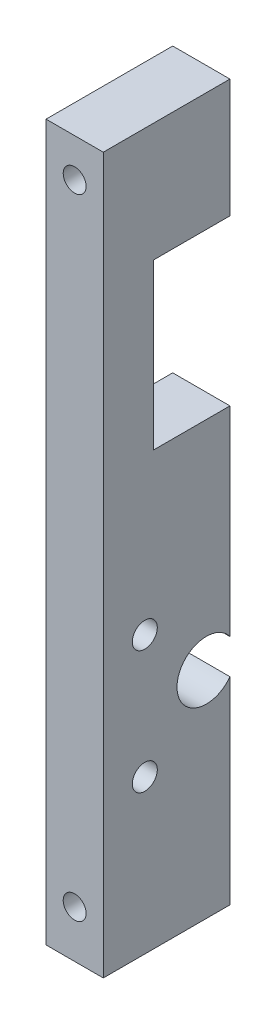
SolidWorks part; units mm, degrees
material "6061-T6 (SS)"
ref_plane "前视基准面" through (0, 0, 0) normal (0, 0, 1) x (1, 0, 0)
ref_plane "上视基准面" through (0, 0, 0) normal (0, 1, 0) x (1, 0, 0)
ref_plane "右视基准面" through (0, 0, 0) normal (1, 0, 0) x (0, 0, -1)
other "Configuration Table"
sketch "草图1" plane through (0, 0, 0) normal (0, 0, 1) x (1, 0, 0)
  line L1 (49.65, -4.3) -> (53.65, -4.3)
  line L2 (49.65, -4.3) -> (49.65, 45.68)
  line L3 (49.65, 45.68) -> (53.65, 45.68)
  line L4 (53.65, -4.3) -> (53.65, 45.68)
  dimension "D1" = 49.65
  dimension "D2" = 53.65
  dimension "D3" = 45.68
  dimension "D4" = 4.3
extrude "Right_RF_Plate" add sketch "草图1" along normal blind 8.8519
move or copy body "Stock_Z_Position" bodies to move or copy 106 copy no translate (0, 0, 2.2481) parameters "D1"=0, "D2"=0, "D3"=2.2481
sketch "草图2" plane through (0, 0, 11.1) normal (0, 0, 1) x (1, 0, 0)
  circle A0 centre (51.65, -1) radius 0.8
  circle A1 centre (51.65, 43) radius 0.8
  dimension "D1" = 1.6
  dimension "D2" = 51.65
  dimension "D3" = 43
  dimension "D4" = 1
extrude "Frame_2xD1p6_Through" cut sketch "草图2" against normal through all
cosmetic thread "Frame_M2_Through_Cosmetic_1" parameters "D2"=2
cosmetic thread "Frame_M2_Through_Cosmetic_2" parameters "D2"=2
sketch "草图3" plane through (53.65, 0, 0) normal (1, 0, 0) x (0, 0, -1)
  circle A0 centre (-3.8995, 10.725) radius 2.05
  dimension "D1" = 4.1
  dimension "D2" = 3.8995
  dimension "D3" = 10.725
extrude "SMA_Center_D4p1" cut sketch "草图3" against normal blind 4
sketch "草图4" plane through (53.65, 0, 0) normal (1, 0, 0) x (0, 0, -1)
  circle A0 centre (-8.1995, 6.425) radius 0.875
  circle A1 centre (-8.1995, 15.025) radius 0.875
  dimension "D1" = 1.75
  dimension "D2" = 8.1995
  dimension "D3" = 6.425
  dimension "D4" = 15.025
extrude "SMA_Upper_2xD1p75_Through" cut sketch "草图4" against normal through all
cosmetic thread "SMA_Upper_Cosmetic_1" parameters "D2"=2.2
cosmetic thread "SMA_Upper_Cosmetic_2" parameters "D2"=2.2
sketch "草图5" plane through (53.65, 0, 0) normal (1, 0, 0) x (0, 0, -1)
  line L1 (-0.9, 25.9) -> (-7.6, 25.9)
  line L2 (-0.9, 25.9) -> (-0.9, 37.4)
  line L3 (-0.9, 37.4) -> (-7.6, 37.4)
  line L4 (-7.6, 25.9) -> (-7.6, 37.4)
  dimension "D1" = 0.9
  dimension "D2" = 7.6
  dimension "D3" = 25.9
  dimension "D4" = 37.4
extrude "TypeC_Window_11p5x6p7" cut sketch "草图5" against normal blind 4
